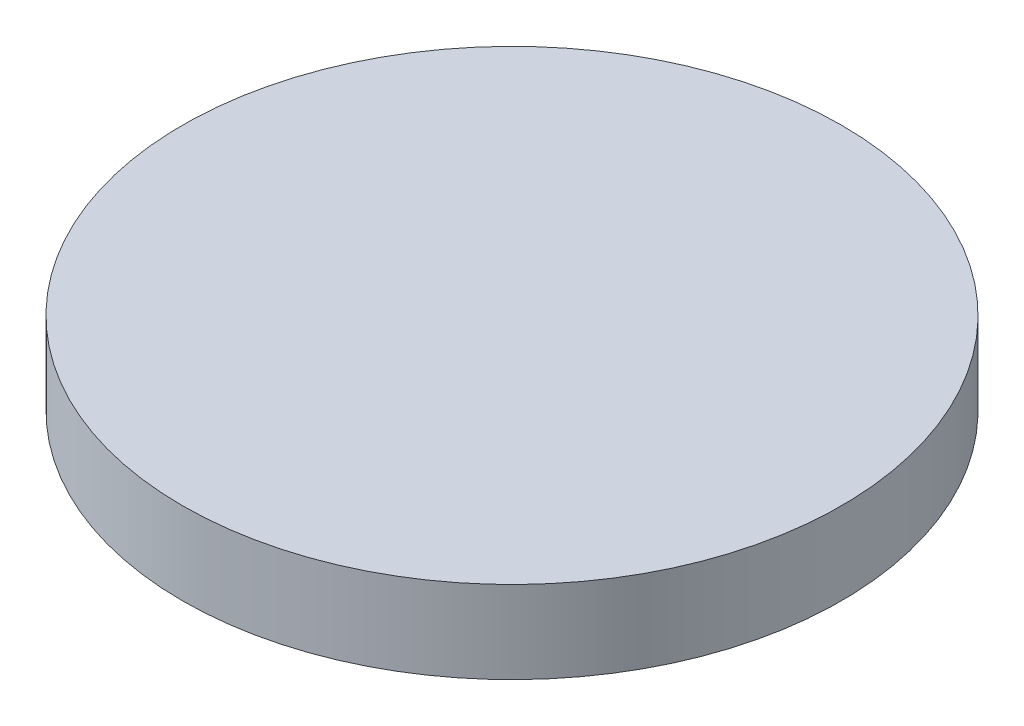
SolidWorks part; units mm, degrees
ref_plane "Front Plane" through (0, 0, 0) normal (0, 0, 1) x (1, 0, 0)
ref_plane "Top Plane" through (0, 0, 0) normal (0, 1, 0) x (1, 0, 0)
ref_plane "Right Plane" through (0, 0, 0) normal (1, 0, 0) x (0, 0, -1)
sketch "Sketch1" plane through (0, 0, 0) normal (0, 1, 0) x (1, 0, 0)
  circle A0 centre (0, 0) radius 38.1
  dimension "D1" = 76.2
extrude "Extrude1" add sketch "Sketch1" along normal blind 9.525
